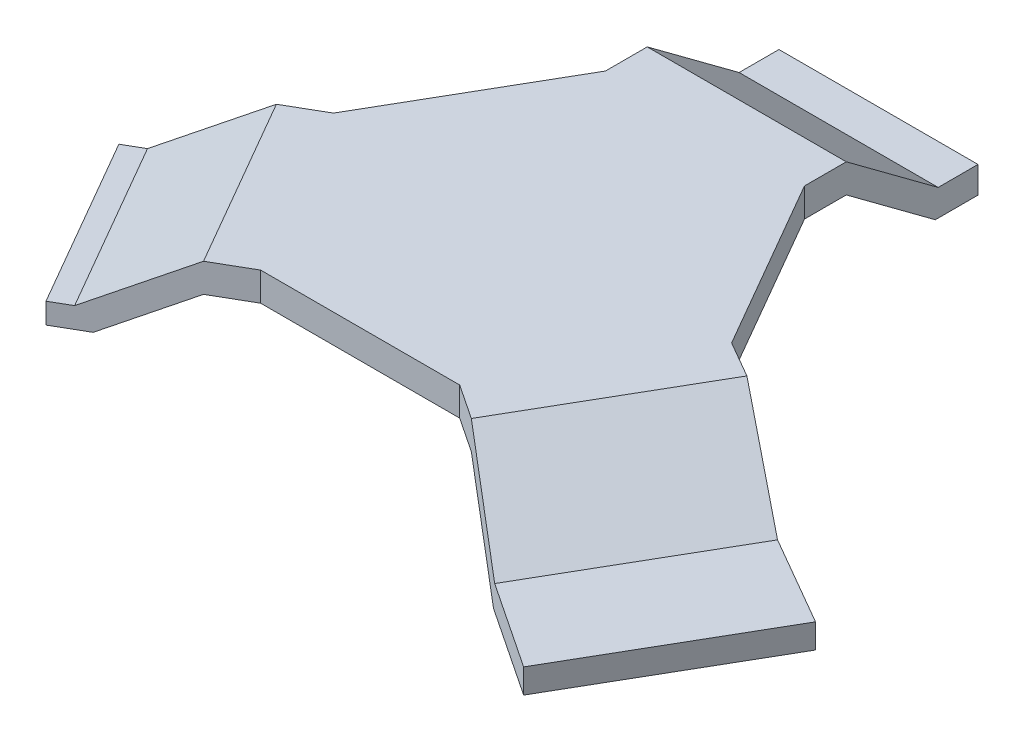
SolidWorks part; units mm, degrees
ref_plane "Front Plane" through (0, 0, 0) normal (0, 0, 1) x (1, 0, 0)
ref_plane "Top Plane" through (0, 0, 0) normal (0, 1, 0) x (1, 0, 0)
ref_plane "Right Plane" through (0, 0, 0) normal (1, 0, 0) x (0, 0, -1)
sketch "Sketch2" plane through (0, 0, 0) normal (0, 1, 0) x (1, 0, 0)
  line L0 (-34.6748, 60.0585) -> (-34.6748, 74.6288)
  line L2 (69.3496, 0) -> (34.6748, 60.0585)
  line L4 (-34.6748, 60.0585) -> (-69.3496, 0)
  line L6 (-34.6748, -60.0585) -> (34.6748, -60.0585)
  line L7 (-34.6748, 74.6288) -> (34.6748, 74.6288)
  line L8 (34.6748, 74.6288) -> (34.6748, 60.0585)
  line L9 (-81.9678, -7.2851) -> (-69.3496, 0)
  line L10 (-81.9678, -7.2851) -> (-47.293, -67.3437)
  line L11 (-47.293, -67.3437) -> (-34.6748, -60.0585)
  line L12 (69.3496, 0) -> (81.9647, -7.2904)
  line L13 (81.9647, -7.2904) -> (46.8021, -68.1344)
  line L14 (46.8021, -68.1344) -> (34.6748, -60.0585)
  line L16 (-69.3496, 0) -> (-52.0122, -30.0293) [skipped]
  line L17 (34.6748, 60.0585) -> (0, 60.0585) [skipped]
  line L18 (34.6748, -60.0585) -> (52.0122, -30.0293) [skipped]
  circle A0 centre (0, 0) radius 60.0585 construction
  point P14 (49.5371, -63.0154)
  point P16 (48.9626, -69.3349)
extrude "Boss-Extrude1" add sketch "Sketch2" along normal blind 10
sketch "Sketch5" plane through (17.3374, 0, 30.0293) normal (0.5, 0, 0.866) x (0.866, 0, -0.5)
  line L0 (-74.6288, 10) -> (-107.5007, -9.4021)
  line L1 (-107.5007, -9.4021) -> (-114.8043, -9.4021)
  line L2 (-114.8043, -9.4021) -> (-114.8043, -16.61)
  line L3 (-114.8043, -16.61) -> (-102.7702, -16.61)
  line L4 (-102.7702, -16.61) -> (-74.6288, 0)
  line L9 (-74.6288, 0) -> (-60.0585, 0)
  line L10 (-60.0585, 0) -> (-60.0585, 10)
  line L11 (-60.0585, 10) -> (-74.6288, 10)
  line L12 (-74.6288, 10) -> (-74.6288, 0)
  line L16 (-74.6288, 10) -> (-74.6288, 0)
  dimension "D1" = 0
extrude "Boss-Extrude3" add sketch "Sketch5" against normal up to surface (69.3496 mm away) up to face at (-75.6587, 5, 3.6426)
sketch "Sketch7" plane through (-34.6748, 0, 0) normal (-1, 0, 0) x (0, 0, 1)
  line L0 (-74.6288, 10) -> (-106.6376, -13.7347)
  line L1 (-106.6376, -13.7347) -> (-120.5156, -13.7347)
  line L2 (-120.5156, -13.7347) -> (-120.5156, -23.0022)
  line L3 (-120.5156, -23.0022) -> (-105.6498, -23.0022)
  line L4 (-105.6498, -23.0022) -> (-74.6288, 0)
  line L5 (-74.6288, 10) -> (-74.6288, 0)
extrude "Boss-Extrude4" add sketch "Sketch7" against normal up to surface (69.3496 mm away) contours L0 L1 L2 L3 L4 L5 up to face at (34.6748, 5, -67.3437)
sketch "Sketch8" plane through (17.3628, 0, -30.0439) normal (0.5004, 0, -0.8658) x (-0.8658, 0, -0.5004)
  line L0 (-74.6141, 10) -> (-103.8183, -19.5162)
  line L1 (-103.8183, -19.5162) -> (-140.0221, -19.5162)
  line L2 (-140.0221, -19.5162) -> (-140.0221, -28.0295)
  line L3 (-140.0221, -28.0295) -> (-102.3474, -28.0295)
  line L4 (-102.3474, -28.0295) -> (-74.6141, 0)
  line L5 (-74.6141, 10) -> (-74.6141, 0)
extrude "Boss-Extrude5" add sketch "Sketch8" against normal up to surface (70.2737 mm away)
